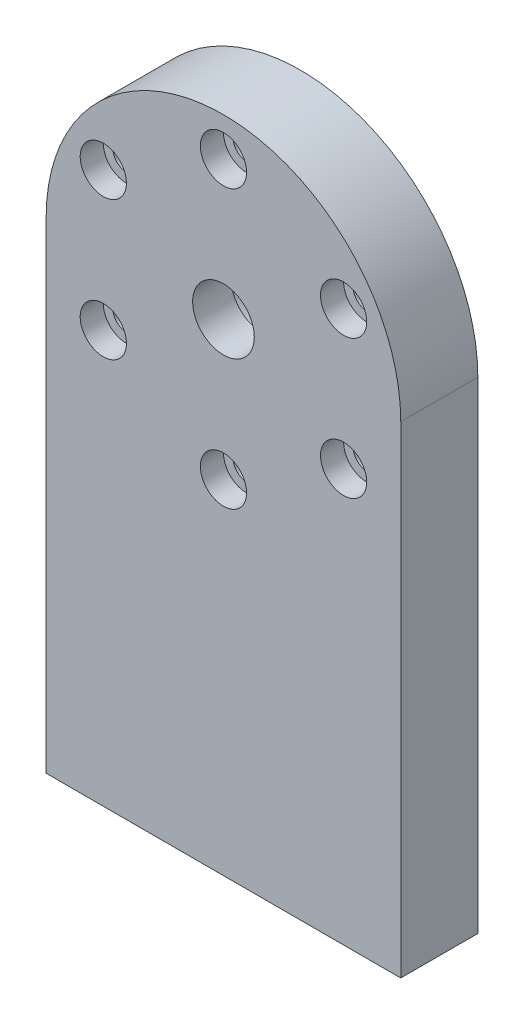
SolidWorks part; units mm, degrees
ref_plane "Front Plane" through (0, 0, 0) normal (0, 0, 1) x (1, 0, 0)
ref_plane "Top Plane" through (0, 0, 0) normal (0, 1, 0) x (1, 0, 0)
ref_plane "Right Plane" through (0, 0, 0) normal (1, 0, 0) x (0, 0, -1)
sketch "Sketch1" plane through (0, 0, 0) normal (0, 0, 1) x (1, 0, 0)
  line L0 (46, 125) -> (46, 0)
  line L1 (46, 0) -> (-46, 0)
  line L2 (-46, 0) -> (-46, 125)
  arc A0 (46, 125) -> (-46, 125) centre (0, 125) ccw
  circle A1 centre (0, 125) radius 8
  dimension "D1" = 92
  dimension "D3" = 16
  dimension "D2" = 125
extrude "Boss-Extrude1" add sketch "Sketch1" along normal mid plane 20
sketch "Sketch3" plane through (0, 0, 10) normal (0, 0, 1) x (1, 0, 0)
  circle A0 centre (0, 125) radius 36 construction
  circle A1 centre (0, 161) radius 3.5
  dimension "D1" = 72
  dimension "D2" = 7
extrude "Cut-Extrude2" cut sketch "Sketch3" against normal through all
sketch "Sketch4" plane through (0, 0, 10) normal (0, 0, 1) x (1, 0, 0)
  circle A0 centre (0, 161) radius 6
  dimension "D1" = 12
extrude "Cut-Extrude3" cut sketch "Sketch4" against normal blind 6
pattern_circular "CirPattern4" count 6 over 360 about axis through (0, 125, 0) along (0, 0, 1) of "Cut-Extrude2", "Cut-Extrude3"
hole_wizard "Tap Drill for M10x1.25 Tap1" positions "Sketch8" profile "Sketch9" hole size "M10x1.25" standard "ISO"
sketch "Sketch8" plane through (0, 0, 0) normal (0, -1, 0) x (-1, 0, 0)
  line L0 (46, -10) -> (-46, -10) construction
  line L1 (-46, -10) -> (-46, 10) construction
  point P0 (-30, 0)
  point P2 (30, 0)
  dimension "D1" = 60
  dimension "D2" = 10
  dimension "D3" = 16
sketch "Sketch9" plane through (30, 0, 0) normal (1, 0, 0) x (0, 0, -1)
  line L0 (0, 0) -> (0, 26.6438)
  line L1 (0, 26.6438) -> (4.4, 24)
  line L2 (4.4, 24) -> (4.4, 0.025)
  line L3 (4.4, 0.025) -> (4.425, 0)
  line L5 (4.425, 0) -> (0, 0)
  line L6 (-4.4, 0.025) -> (-4.425, 0) construction
  line L10 (0, 26.6438) -> (-4.4, 24) construction
  line L11 (0, -6.35) -> (0, 107.95) construction
  dimension "Hole Dia." = 8.8
  dimension "Hole Depth" = 24
  dimension "Near C'Sink Dia." = 8.85
  dimension "Near C'Sink Angle" = 90
  dimension "Drill Angle" = 118
sketch "Sketch10" plane through (0, 0, -10) normal (0, 0, -1) x (-1, 0, 0)
  circle A0 centre (0, 125) radius 12.5
  dimension "D1" = 25
extrude "Cut-Extrude4" cut sketch "Sketch10" against normal blind 10
